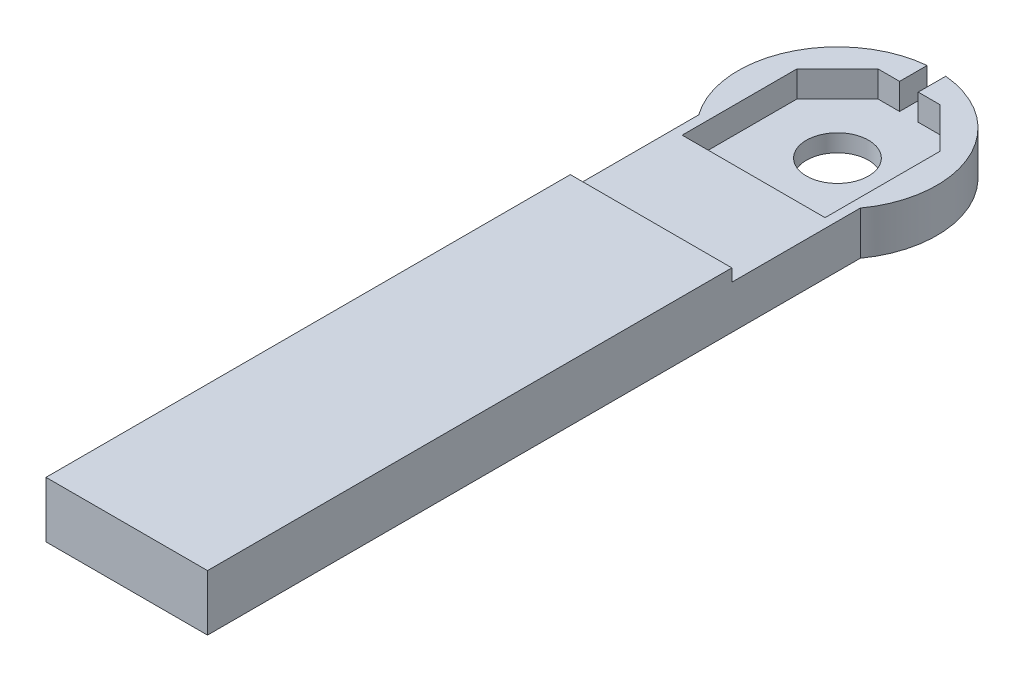
SolidWorks part; units mm, degrees
ref_plane "Front Plane" through (0, 0, 0) normal (0, 0, 1) x (1, 0, 0)
ref_plane "Top Plane" through (0, 0, 0) normal (0, 1, 0) x (1, 0, 0)
ref_plane "Right Plane" through (0, 0, 0) normal (1, 0, 0) x (0, 0, -1)
sketch "Sketch1" plane through (0, 0, 0) normal (0, 1, 0) x (1, 0, 0)
  line L0 (-5.75, -999.648) -> (-5.75, 49000.352) construction
  line L1 (5.75, -999.7466) -> (5.75, 49000.2534) construction
  line L2 (-1004.7888, 5.75) -> (-0.75, 5.75) construction
  line L3 (-1005.0845, -6.75) -> (48994.9155, -6.75) construction
  line L4 (0, 0) -> (0, 5.75) construction
  line L5 (-2.5, 5.75) -> (-0.75, 5.75)
  line L6 (-0.75, 5.75) -> (-0.75, 7.9648)
  line L7 (0.75, 5.75) -> (0.75, 7.9648)
  line L8 (-1002.9652, 2.5) -> (48997.0348, 2.5) construction
  line L9 (-5.75, 2.5) -> (-2.5, 5.75)
  line L10 (2.5, 5.75) -> (5.75, 2.5)
  line L12 (-8, -20) -> (8, -20)
  line L14 (-5.75, 2.5) -> (-5.75, -6.75)
  line L15 (-5.75, -6.75) -> (5.75, -6.75)
  line L16 (5.75, -6.75) -> (5.75, 2.5)
  line L17 (0.75, 5.75) -> (48995.2112, 5.75) construction
  line L18 (0.75, 5.75) -> (2.5, 5.75)
  line L19 (-6.5, -4.6637) -> (-6.5, -15)
  line L20 (-6.5, -15) -> (6.5, -15)
  line L21 (6.5, -15) -> (6.5, -4.6637)
  arc A0 (6.5, -4.6637) -> (-6.5, -4.6637) centre (0, 0) ccw
  arc A1 (-0.75, 7.9648) -> (0.75, 7.9648) centre (0, 0) cw
  point P15 (0, 5.75)
  dimension "D1" = 16
  dimension "D2" = 6.75
  dimension "D3" = 11.5
  dimension "D4" = 5.75
  dimension "D5" = 5.75
  dimension "D6" = 5
  dimension "D7" = 0.75
  dimension "D8" = 0.75
  dimension "D9" = 2.5
  dimension "D10" = 13
  dimension "D11" = 2.5
  dimension "D12" = 6.5
  dimension "D13" = 15
extrude "Boss-Extrude1" add sketch "Sketch1" along normal blind 2.1
sketch "Sketch2" plane through (0, 0, 0) normal (0, 1, 0) x (1, 0, 0)
  line L0 (6.5, -4.6637) -> (6.5, -15)
  line L1 (6.5, -15) -> (-6.5, -15)
  line L2 (-6.5, -15) -> (-6.5, -4.6637)
  line L3 (-5.75, 2.5) -> (-5.75, -6.75) construction
  line L4 (5.75, -6.75) -> (5.75, 2.5) construction
  line L5 (-6.5, -4.6637) -> (-6.5, -15) construction
  line L6 (-5, -5.5) -> (-5, -6.75)
  line L7 (-5, -6.75) -> (-3.5, -6.75)
  line L8 (-3.5, -6.75) -> (-3.5, -5.5)
  line L9 (3.5, -5.5) -> (3.5, -6.75)
  line L10 (3.5, -6.75) -> (5, -6.75)
  line L11 (5, -6.75) -> (5, -5.5)
  line L12 (6.5, -15) -> (6.5, -4.6637) construction
  line L13 (-6.5, -15) -> (6.5, -15) construction
  arc A0 (6.5, -4.6637) -> (-6.5, -4.6637) centre (0, 0) ccw
  arc A1 (6.5, -4.6637) -> (-6.5, -4.6637) centre (0, 0) ccw construction
  circle A2 centre (0, 0) radius 2.5
  arc A3 (-3.5, -5.5) -> (-5, -5.5) centre (-4.25, -5.5) ccw
  arc A4 (5, -5.5) -> (3.5, -5.5) centre (4.25, -5.5) ccw
  arc A5 (6.5, -4.6637) -> (0.75, 7.9648) centre (0, 0) ccw construction
  dimension "D1" = 5
  dimension "D6" = 1.5
  dimension "D7" = 1.5
  dimension "D2" = 1.5
  dimension "D3" = 1.5
  dimension "D4" = 5.5
  dimension "D5" = 5.5
  dimension "D8" = 1.25
  dimension "D9" = 1.25
extrude "Boss-Extrude2" add sketch "Sketch2" against normal blind 1.4
ref_plane "Plane1" through (0, 0, 57.2) normal (0, 0, 1) x (1, 0, 0)
sketch "Sketch4" plane through (0, 0, 15) normal (0, 0, 1) x (1, 0, 0)
  line L0 (6.5, 2.1) -> (6.5, -1.4) construction
  line L1 (-6.5, -1.4) -> (6.5, -1.4)
  line L2 (-6.5, -1.4) -> (-6.5, 3.1)
  line L3 (-6.5, 3.1) -> (6.5, 3.1)
  line L4 (6.5, -1.4) -> (6.5, 3.1)
  dimension "D1" = 4.5
extrude "Boss-Extrude3" add sketch "Sketch4" along normal up to surface (42.2 mm away) up to plane "Plane1"
